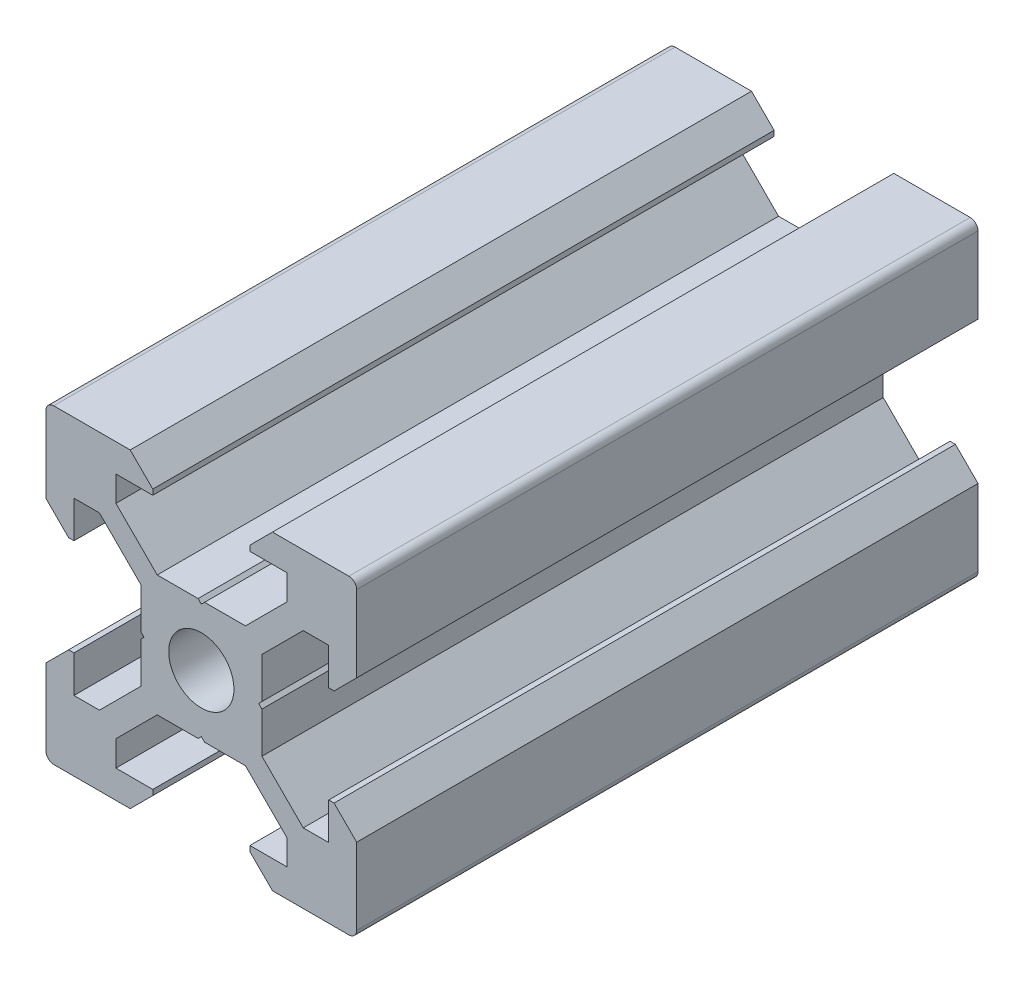
SolidWorks part; units mm, degrees
material "6061-T6 (SS)"
ref_plane "Front Plane" through (0, 0, 0) normal (0, 0, 1) x (1, 0, 0)
ref_plane "Top Plane" through (0, 0, 0) normal (0, 1, 0) x (1, 0, 0)
ref_plane "Right Plane" through (0, 0, 0) normal (1, 0, 0) x (0, 0, -1)
ref_plane "Plane1" through (0, 0, 0) normal (0, 0, -1) x (-1, 0, 0)
sketch "Sketch1" plane through (0, 0, 0) normal (0, 0, -1) x (-1, 0, 0)
  line L0 (-3.9, -0.21) -> (-3.9, -2.8393)
  line L1 (-3.9, -2.8393) -> (-6.5607, -5.5)
  line L2 (-6.5607, -5.5) -> (-8.2, -5.5)
  line L3 (-8.2, -5.5) -> (-8.2, -3.125)
  line L4 (-8.2, -3.125) -> (-8.545, -3.125)
  line L5 (-8.545, -3.125) -> (-10, -4.58)
  line L6 (-10, -4.58) -> (-10, -9.5)
  line L7 (-9.5, -10) -> (-4.58, -10)
  line L8 (-4.58, -10) -> (-3.125, -8.545)
  line L9 (-3.125, -8.545) -> (-3.125, -8.2)
  line L10 (-3.125, -8.2) -> (-5.5, -8.2)
  line L11 (-5.5, -8.2) -> (-5.5, -6.5607)
  line L12 (-5.5, -6.5607) -> (-2.8393, -3.9)
  line L13 (-2.8393, -3.9) -> (-0.21, -3.9)
  line L14 (-0.21, -3.9) -> (0, -3.69)
  line L15 (0, -3.69) -> (0.21, -3.9)
  line L16 (0.21, -3.9) -> (2.8393, -3.9)
  line L17 (2.8393, -3.9) -> (5.5, -6.5607)
  line L18 (5.5, -6.5607) -> (5.5, -8.2)
  line L19 (5.5, -8.2) -> (3.125, -8.2)
  line L20 (3.125, -8.2) -> (3.125, -8.545)
  line L21 (3.125, -8.545) -> (4.58, -10)
  line L22 (4.58, -10) -> (9.5, -10)
  line L23 (10, -9.5) -> (10, -4.58)
  line L24 (10, -4.58) -> (8.545, -3.125)
  line L25 (8.545, -3.125) -> (8.2, -3.125)
  line L26 (8.2, -3.125) -> (8.2, -5.5)
  line L27 (8.2, -5.5) -> (6.5607, -5.5)
  line L28 (6.5607, -5.5) -> (3.9, -2.8393)
  line L29 (3.9, -2.8393) -> (3.9, -0.21)
  line L30 (3.9, -0.21) -> (3.69, 0)
  line L31 (3.69, 0) -> (3.9, 0.21)
  line L32 (3.9, 0.21) -> (3.9, 2.8393)
  line L33 (3.9, 2.8393) -> (6.5607, 5.5)
  line L34 (6.5607, 5.5) -> (8.2, 5.5)
  line L35 (8.2, 5.5) -> (8.2, 3.125)
  line L36 (8.2, 3.125) -> (8.545, 3.125)
  line L37 (8.545, 3.125) -> (10, 4.58)
  line L38 (10, 4.58) -> (10, 9.5)
  line L39 (9.5, 10) -> (4.58, 10)
  line L40 (4.58, 10) -> (3.125, 8.545)
  line L41 (3.125, 8.545) -> (3.125, 8.2)
  line L42 (3.125, 8.2) -> (5.5, 8.2)
  line L43 (5.5, 8.2) -> (5.5, 6.5607)
  line L44 (5.5, 6.5607) -> (2.8393, 3.9)
  line L45 (2.8393, 3.9) -> (0.21, 3.9)
  line L46 (0.21, 3.9) -> (0, 3.69)
  line L47 (0, 3.69) -> (-0.21, 3.9)
  line L48 (-0.21, 3.9) -> (-2.8393, 3.9)
  line L49 (-2.8393, 3.9) -> (-5.5, 6.5607)
  line L50 (-5.5, 6.5607) -> (-5.5, 8.2)
  line L51 (-5.5, 8.2) -> (-3.125, 8.2)
  line L52 (-3.125, 8.2) -> (-3.125, 8.545)
  line L53 (-3.125, 8.545) -> (-4.58, 10)
  line L54 (-4.58, 10) -> (-9.5, 10)
  line L55 (-10, 9.5) -> (-10, 4.58)
  line L56 (-10, 4.58) -> (-8.545, 3.125)
  line L57 (-8.545, 3.125) -> (-8.2, 3.125)
  line L58 (-8.2, 3.125) -> (-8.2, 5.5)
  line L59 (-8.2, 5.5) -> (-6.5607, 5.5)
  line L60 (-6.5607, 5.5) -> (-3.9, 2.8393)
  line L61 (-3.9, 2.8393) -> (-3.9, 0.21)
  line L62 (-3.9, 0.21) -> (-3.69, 0)
  line L63 (-3.69, 0) -> (-3.9, -0.21)
  circle A0 centre (0, 0) radius 2.1
  arc A1 (-10, -9.5) -> (-9.5, -10) centre (-9.5, -9.5) ccw
  arc A2 (9.5, -10) -> (10, -9.5) centre (9.5, -9.5) ccw
  arc A3 (10, 9.5) -> (9.5, 10) centre (9.5, 9.5) ccw
  arc A4 (-9.5, 10) -> (-10, 9.5) centre (-9.5, 9.5) ccw
extrude "Boss-Extrude1" add sketch "Sketch1" against normal blind 40
